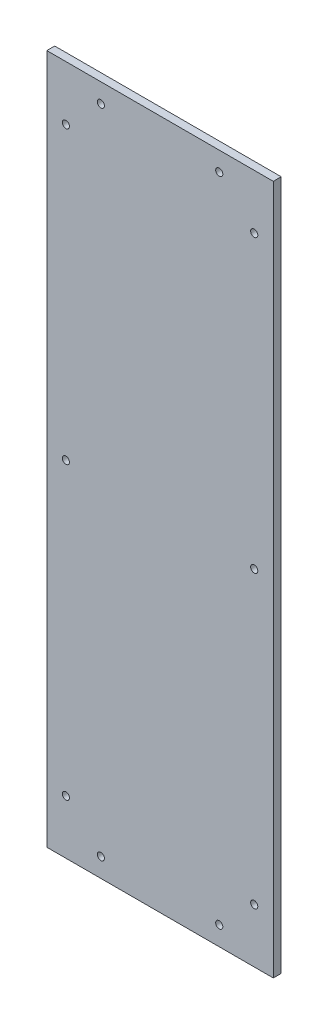
SolidWorks part; units mm, degrees
ref_plane "Front Plane" through (0, 0, 0) normal (0, 0, 1) x (1, 0, 0)
ref_plane "Top Plane" through (0, 0, 0) normal (0, 1, 0) x (1, 0, 0)
ref_plane "Right Plane" through (0, 0, 0) normal (1, 0, 0) x (0, 0, -1)
sketch "Sketch1" plane through (0, 0, 0) normal (0, 0, 1) x (1, 0, 0)
  line L1 (-124.8164, 208.5127) -> (11.7086, 208.5127)
  line L2 (-124.8164, 208.5127) -> (-124.8164, -207.4123)
  line L3 (-124.8164, -207.4123) -> (11.7086, -207.4123)
  line L4 (11.7086, 208.5127) -> (11.7086, -207.4123)
  dimension "D1" = 415.925
  dimension "D2" = 136.525
extrude "Boss-Extrude1" add sketch "Sketch1" along normal blind 4.7625
hole_wizard "#8 Clearance Hole1" positions "Sketch2" profile "Sketch3" hole size "#8" standard "ANSI Inch" end condition through all
sketch "Sketch2" plane through (0, 0, 0) normal (0, 0, -1) x (-1, 0, 0)
  point P0 (92.2409, -195.9188)
  point P3 (113.3229, -174.8368)
  point P6 (20.8669, -195.9188)
  point P9 (-0.2151, -174.8368)
  point P12 (113.3229, 0.4232)
  point P15 (92.2409, 197.0192)
  point P18 (20.8669, 197.0192)
  point P21 (-0.2151, 0.4232)
  point P24 (113.3229, 175.6832)
  point P27 (-0.2151, 175.6832)
sketch "Sketch3" plane through (-92.2409, -195.9188, 0) normal (1, 0, 0) x (0, 1, 0)
  line L0 (0, 0) -> (0, 4.7625)
  line L1 (0, 4.7625) -> (2.1526, 4.7625)
  line L2 (2.1526, 4.7625) -> (2.1526, 0)
  line L5 (2.1526, 0) -> (0, 0)
  line L11 (0, -6.35) -> (0, 107.95) construction
  dimension "Thru Hole Dia." = 4.3053
  dimension "Thru Hole Depth" = 4.7625
